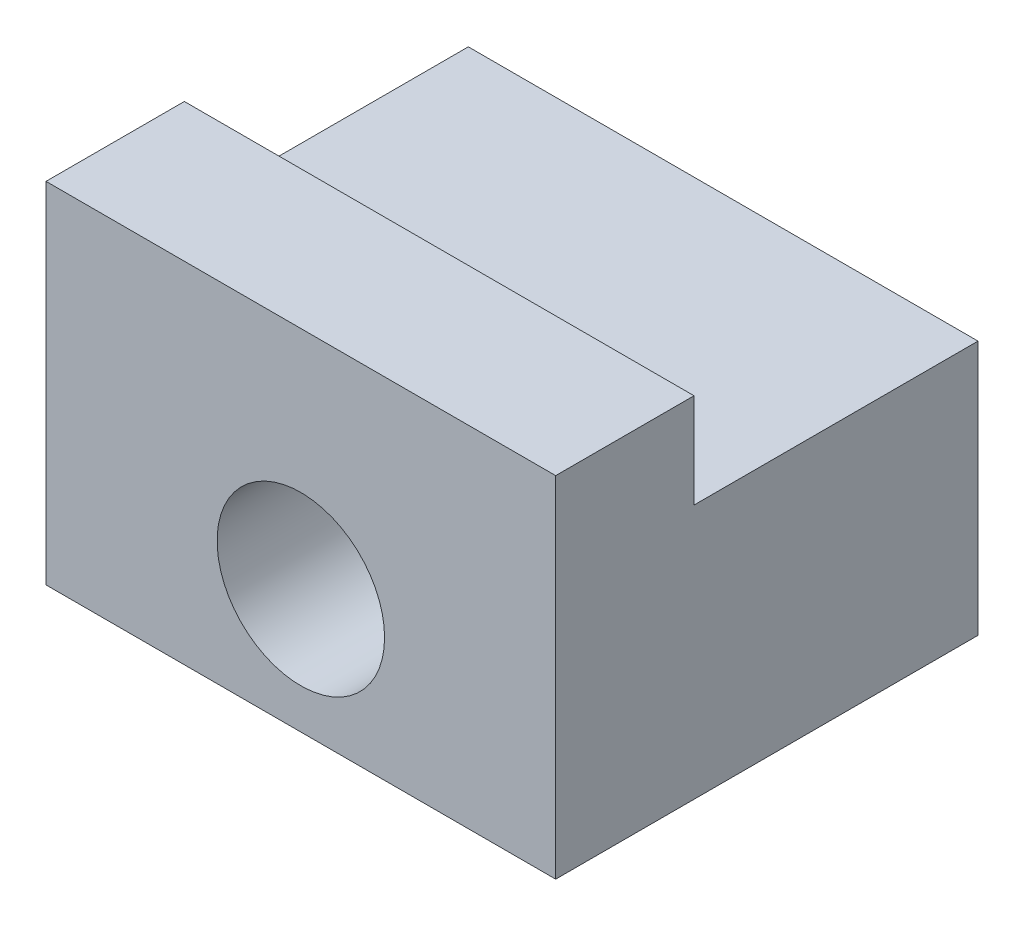
SolidWorks part; units mm, degrees
ref_plane "前视基准面" through (0, 0, 0) normal (0, 0, 1) x (1, 0, 0)
ref_plane "上视基准面" through (0, 0, 0) normal (0, 1, 0) x (1, 0, 0)
ref_plane "右视基准面" through (0, 0, 0) normal (1, 0, 0) x (0, 0, -1)
other "Configuration Table"
sketch "M2 screw clip body profile" plane through (0, 0, 0) normal (0, 0, 1) x (1, 0, 0)
  line L0 (-3.5, -1.7) -> (3.5, -1.7)
  line L1 (3.5, -1.7) -> (3.5, 1.8)
  line L2 (3.5, 1.8) -> (-3.5, 1.8)
  line L3 (-3.5, 1.8) -> (-3.5, -1.7)
  circle A0 centre (0, 0) radius 1.15
extrude "M2 screw clip body" add sketch "M2 screw clip body profile" along normal blind 5.8
sketch "Board edge retaining toe profile" plane through (0, 0, 0) normal (0, 0, 1) x (1, 0, 0)
  line L0 (-3.5, 1.8) -> (3.5, 1.8)
  line L1 (3.5, 1.8) -> (3.5, 3.1)
  line L2 (3.5, 3.1) -> (-3.5, 3.1)
  line L3 (-3.5, 3.1) -> (-3.5, 1.8)
extrude "Board edge retaining toe" add sketch "Board edge retaining toe profile" along normal blind 1.9 from offset 3.9
